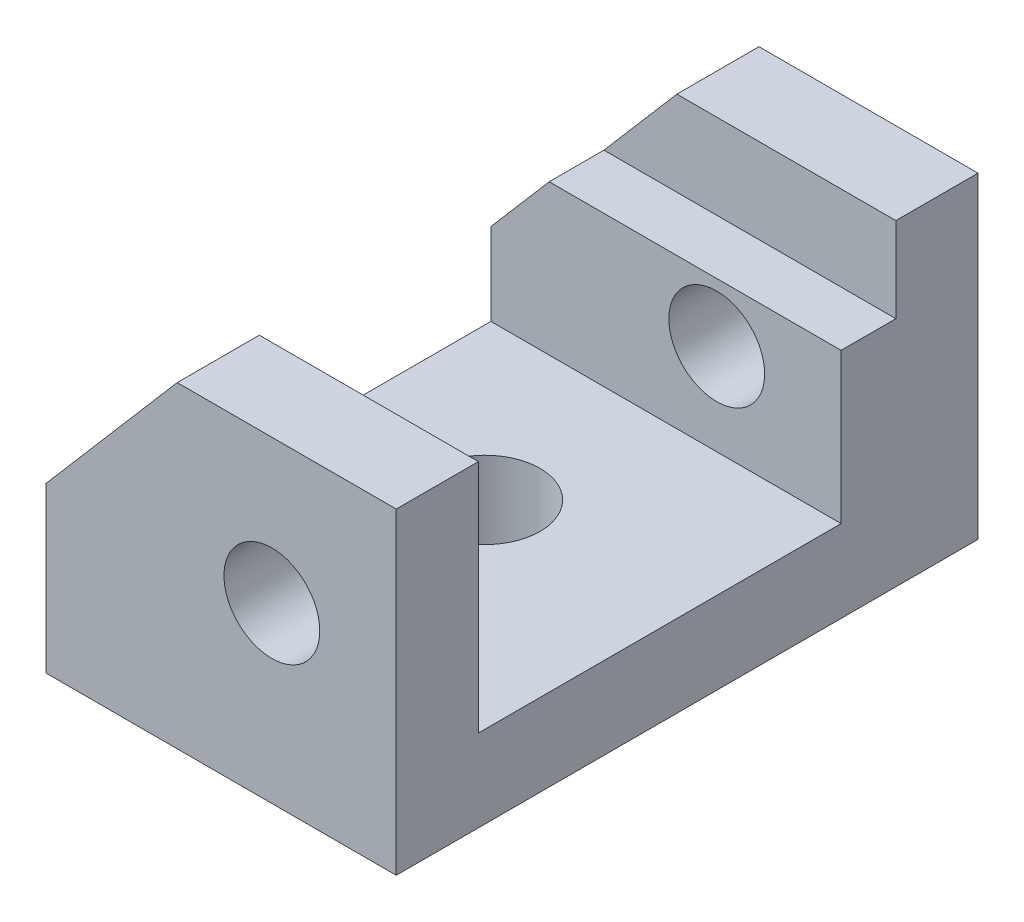
SolidWorks part; units mm, degrees
ref_plane "정면" through (0, 0, 0) normal (0, 0, 1) x (1, 0, 0)
ref_plane "윗면" through (0, 0, 0) normal (0, 1, 0) x (1, 0, 0)
ref_plane "우측면" through (0, 0, 0) normal (1, 0, 0) x (0, 0, -1)
sketch "스케치1" plane through (0, 0, 0) normal (0, 0, 1) x (1, 0, 0)
  line L0 (-23.3518, -14) -> (-4.1794, 8.3448)
  line L1 (-4.1794, 8.3448) -> (27.8206, 8.3448)
  line L2 (27.8206, 8.3448) -> (27.8206, -38)
  line L3 (27.8206, -38) -> (-23.3518, -38)
  line L4 (-23.3518, -38) -> (-23.3518, -14)
  circle A0 centre (9.6482, -12.6552) radius 7
  dimension "D3" = 14
  dimension "D1" = 32
  dimension "D2" = 24
  dimension "D4" = 21
  dimension "D5" = 33
extrude "보스-돌출1" add sketch "스케치1" along normal blind 85
sketch "스케치2" plane through (-23.3518, 0, 0) normal (-1, 0, 0) x (0, 0, 1)
  line L0 (85, 8.3448) -> (0, 8.3448) construction
  line L1 (12, 8.3448) -> (12, -4.072)
  line L2 (12, -4.072) -> (20, -4.072)
  line L3 (20, -4.072) -> (20, -26)
  line L4 (20, -26) -> (73, -26)
  line L5 (73, -26) -> (73, 8.3448)
  line L6 (73, 8.3448) -> (12, 8.3448)
  line L8 (85, -38) -> (0, -38) construction
  dimension "D1" = 12
  dimension "D2" = 12
  dimension "D3" = 8
  dimension "D4" = 12
extrude "컷-돌출1" cut sketch "스케치2" against normal through all contours L6 L1 L2 L3 L4 L5
sketch "스케치3" plane through (0, -26, 0) normal (0, 1, 0) x (1, 0, 0)
  circle A0 centre (-1.1794, -43) radius 8
  dimension "D1" = 16
  dimension "D2" = 43
  dimension "D3" = 29
extrude "컷-돌출2" cut sketch "스케치3" against normal through all contours A0
